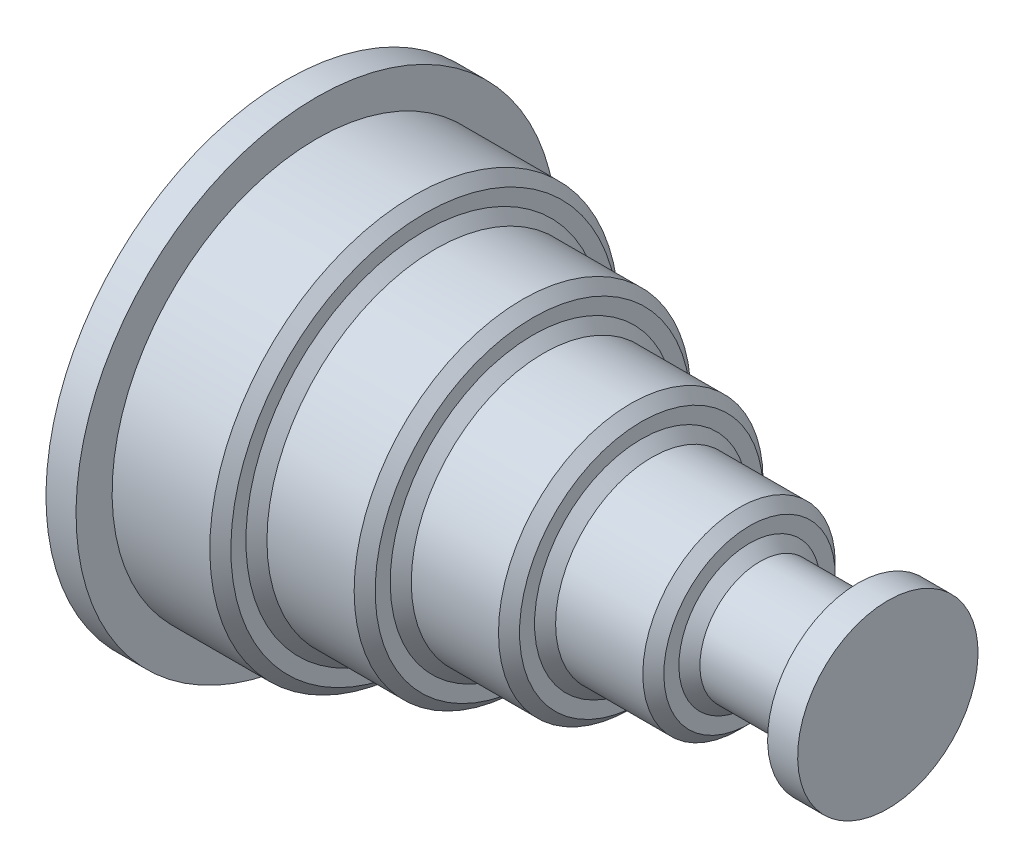
SolidWorks part; units mm, degrees
ref_plane "Front" through (0, 0, 0) normal (0, 0, 1) x (1, 0, 0)
ref_plane "Top" through (0, 0, 0) normal (0, 1, 0) x (1, 0, 0)
ref_plane "Right" through (0, 0, 0) normal (1, 0, 0) x (0, 0, -1)
sketch "Sketch1" plane through (0, 0, 0) normal (0, 0, 1) x (1, 0, 0)
  line L0 (0, 0) -> (0, 8)
  line L1 (0, 8) -> (1, 8)
  line L2 (20, 3) -> (20, 0)
  line L3 (20, 0) -> (0, 0)
  line L4 (1, 8) -> (1, 6.8)
  line L5 (1, 6.8) -> (4.6, 6.8)
  line L6 (4.6, 6.8) -> (4.6, 5.6)
  line L7 (4.6, 5.6) -> (8.2, 5.6)
  line L8 (8.2, 5.6) -> (8.2, 4.4)
  line L9 (8.2, 4.4) -> (11.8, 4.4)
  line L10 (11.8, 4.4) -> (11.8, 3.2)
  line L11 (11.8, 3.2) -> (15.4, 3.2)
  line L12 (15.4, 3.2) -> (15.4, 2)
  line L13 (15.4, 2) -> (19, 2)
  line L14 (19, 2) -> (19, 3)
  line L15 (19, 3) -> (20, 3)
  dimension "D1" = 8
  dimension "D2" = 3
  dimension "D3" = 20
  dimension "D4" = 1
  dimension "D5" = 2
revolve "Revolve1" add sketch "Sketch1" angle 360 about L3
chamfer "Chamfer1" distance 0.35 angle 45 8 edges at (15.4, 2, 0) (11.8, 3.2, 0) (8.2, 4.4, 0) (4.6, 5.6, 0) (15.4, 3.2, 0) (11.8, 4.4, 0) (8.2, 5.6, 0) (4.6, 6.8, 0)
